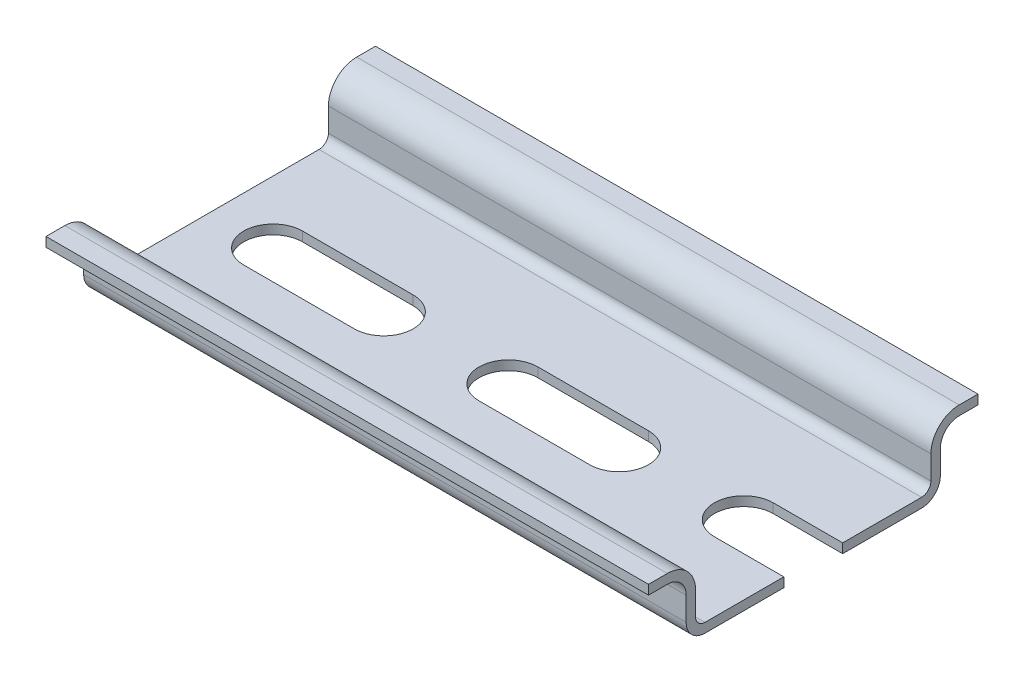
SolidWorks part; units mm, degrees
ref_plane "Front Plane" through (0, 0, 0) normal (0, 0, 1) x (1, 0, 0)
ref_plane "Top Plane" through (0, 0, 0) normal (0, 1, 0) x (1, 0, 0)
ref_plane "Right Plane" through (0, 0, 0) normal (1, 0, 0) x (0, 0, -1)
sketch "Sketch1" plane through (0, 0, 0) normal (1, 0, 0) x (0, 0, -1)
  line L0 (0, 0) -> (0, 18.2344) construction
  line L1 (0, 0) -> (26.621, 0) construction
  line L2 (-11.5, 0) -> (11.5, 0)
  line L3 (13.5, 2) -> (13.5, 4.5)
  line L4 (15.5, 6.5) -> (17.5, 6.5)
  line L5 (-13.5, 2) -> (-13.5, 4.5)
  line L6 (-15.5, 6.5) -> (-17.5, 6.5)
  arc A0 (13.5, 2) -> (11.5, 0) centre (11.5, 2) cw
  arc A1 (15.5, 6.5) -> (13.5, 4.5) centre (15.5, 4.5) ccw
  arc A2 (-13.5, 2) -> (-11.5, 0) centre (-11.5, 2) ccw
  arc A3 (-15.5, 6.5) -> (-13.5, 4.5) centre (-15.5, 4.5) cw
  point P9 (13.5, 0)
  dimension "D1" = 2
  dimension "D3" = 2
  dimension "D2" = 6.5
  dimension "D4" = 35
  dimension "D5" = 27
extrude "Extrude-Thin1" add sketch "Sketch1" along normal blind 37.5 and the other way blind 37.5 thin thin type one direction wall 1
sketch "Sketch2" plane through (0, 0, 0) normal (0, -1, 0) x (1, 0, 0)
  line L0 (0, 6.6969) -> (0, 0) construction
  line L1 (0, 0) -> (9.9599, 0) construction
  line L2 (-5.875, 3.125) -> (5.875, 3.125)
  line L3 (-5.875, -3.125) -> (5.875, -3.125)
  arc A0 (5.875, 3.125) -> (5.875, -3.125) centre (5.875, 0) cw
  arc A1 (-5.875, 3.125) -> (-5.875, -3.125) centre (-5.875, 0) ccw
  point P6 (0, 3.125)
  point P12 (0, -3.125)
  dimension "D2" = 11.75
  dimension "D1" = 6.25
extrude "Cut-Extrude1" cut sketch "Sketch2" against normal up to next
pattern_linear "LPattern1" count 2 spacing 25 along (1, 0, 0) count 2 spacing 25 along (-1, 0, 0) of "Cut-Extrude1"
sketch "Skizze1" plane through (37.5, 0, 0) normal (1, 0, 0) x (0, 0, -1)
  line L12 (-15.5, 7.5) -> (-17.5, 7.5)
  line L13 (-17.5, 7.5) -> (-17.5, 6.5)
  line L14 (-17.5, 6.5) -> (-15.5, 6.5)
  line L15 (-13.5, 4.5) -> (-13.5, 2)
  line L16 (-11.5, 0) -> (11.5, 0)
  line L17 (13.5, 2) -> (13.5, 4.5)
  line L18 (15.5, 6.5) -> (17.5, 6.5)
  line L19 (17.5, 6.5) -> (17.5, 7.5)
  line L20 (17.5, 7.5) -> (15.5, 7.5)
  line L21 (12.5, 4.5) -> (12.5, 2)
  line L22 (11.5, 1) -> (-11.5, 1)
  line L23 (-12.5, 2) -> (-12.5, 4.5)
  line L24 (-15.5, 7.5) -> (-17.5, 7.5)
  line L25 (-17.5, 7.5) -> (-17.5, 6.5)
  line L26 (-17.5, 6.5) -> (-15.5, 6.5)
  line L27 (-13.5, 4.5) -> (-13.5, 2)
  line L28 (-11.5, 0) -> (11.5, 0)
  line L29 (13.5, 2) -> (13.5, 4.5)
  line L30 (15.5, 6.5) -> (17.5, 6.5)
  line L31 (17.5, 6.5) -> (17.5, 7.5)
  line L32 (17.5, 7.5) -> (15.5, 7.5)
  line L33 (12.5, 4.5) -> (12.5, 2)
  line L34 (11.5, 1) -> (-11.5, 1)
  line L35 (-12.5, 2) -> (-12.5, 4.5)
  arc A8 (-13.5, 4.5) -> (-15.5, 6.5) centre (-15.5, 4.5) ccw
  arc A9 (-13.5, 2) -> (-11.5, 0) centre (-11.5, 2) ccw
  arc A10 (11.5, 0) -> (13.5, 2) centre (11.5, 2) ccw
  arc A11 (15.5, 6.5) -> (13.5, 4.5) centre (15.5, 4.5) ccw
  arc A12 (15.5, 7.5) -> (12.5, 4.5) centre (15.5, 4.5) ccw
  arc A13 (11.5, 1) -> (12.5, 2) centre (11.5, 2) ccw
  arc A14 (-12.5, 2) -> (-11.5, 1) centre (-11.5, 2) ccw
  arc A15 (-12.5, 4.5) -> (-15.5, 7.5) centre (-15.5, 4.5) ccw
  arc A16 (-13.5, 4.5) -> (-15.5, 6.5) centre (-15.5, 4.5) ccw
  arc A17 (-13.5, 2) -> (-11.5, 0) centre (-11.5, 2) ccw
  arc A18 (11.5, 0) -> (13.5, 2) centre (11.5, 2) ccw
  arc A19 (15.5, 6.5) -> (13.5, 4.5) centre (15.5, 4.5) ccw
  arc A20 (15.5, 7.5) -> (12.5, 4.5) centre (15.5, 4.5) ccw
  arc A21 (11.5, 1) -> (12.5, 2) centre (11.5, 2) ccw
  arc A22 (-12.5, 2) -> (-11.5, 1) centre (-11.5, 2) ccw
  arc A23 (-12.5, 4.5) -> (-15.5, 7.5) centre (-15.5, 4.5) ccw
  dimension "D1" = 0
extrude "Schnitt-Linear austragen1" cut sketch "Skizze1" against normal blind 11
